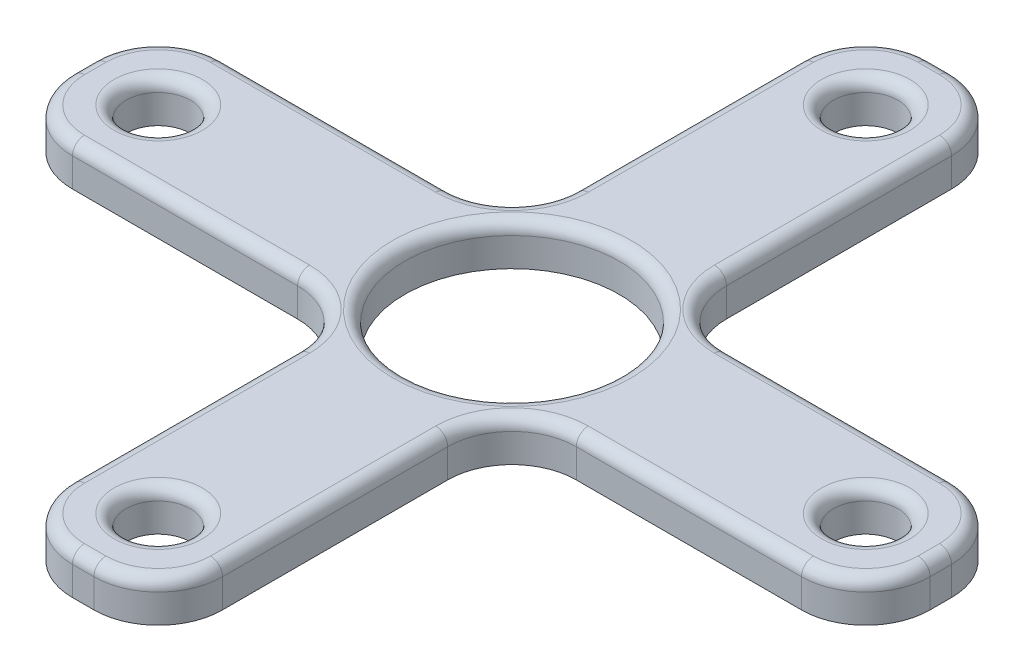
SolidWorks part; units mm, degrees
ref_plane "Front Plane" through (0, 0, 0) normal (0, 0, 1) x (1, 0, 0)
ref_plane "Top Plane" through (0, 0, 0) normal (0, 1, 0) x (1, 0, 0)
ref_plane "Right Plane" through (0, 0, 0) normal (1, 0, 0) x (0, 0, -1)
sketch "Sketch1" plane through (0, 0, 0) normal (0, 1, 0) x (1, 0, 0)
  line L0 (-7.1392, 20) -> (-7.1392, 18) construction
  line L1 (12.8608, 0) -> (10.8608, 0) construction
  line L2 (-27.1392, 0) -> (-25.1392, 0) construction
  line L3 (-7.1392, 20) -> (-3.6392, 20)
  line L4 (-7.1392, 20) -> (-10.6392, 20)
  line L5 (-27.1392, 0) -> (-27.1392, 3.5)
  line L6 (-10.6392, 20) -> (-10.6392, 3.5)
  line L7 (-10.6392, 3.5) -> (-27.1392, 3.5)
  line L8 (-3.6392, 20) -> (-3.6392, 3.5)
  line L9 (-3.6392, 3.5) -> (12.8608, 3.5)
  line L10 (12.8608, 3.5) -> (12.8608, 0)
  line L11 (12.8608, 0) -> (12.8608, -3.5)
  line L12 (12.8608, -3.5) -> (-3.6392, -3.5)
  line L13 (-3.6392, -3.5) -> (-3.6392, -20)
  line L14 (-3.6392, -20) -> (-7.1392, -20)
  line L15 (-7.1392, -20) -> (-10.6392, -20)
  line L16 (-10.6392, -20) -> (-10.6392, -3.5)
  line L17 (-10.6392, -3.5) -> (-27.1392, -3.5)
  line L18 (-27.1392, -3.5) -> (-27.1392, 0)
  line L19 (-7.1392, -20) -> (-7.1392, -18) construction
  line L20 (-7.1392, 0) -> (-4.0464, 0) construction
  line L21 (-7.1392, 0) -> (-7.1392, 3.0617) construction
  line L22 (-25.1392, 0) -> (-23.6392, 0) construction
  line L23 (-7.1392, 18) -> (-7.1392, 16.5) construction
  line L24 (10.8608, 0) -> (9.3608, 0) construction
  line L25 (-7.1392, -18) -> (-7.1392, -16.5) construction
  circle A0 centre (-23.6392, 0) radius 1.5
  circle A1 centre (-7.1392, 16.5) radius 1.5
  circle A2 centre (9.3608, 0) radius 1.5
  circle A3 centre (-7.1392, -16.5) radius 1.5
  dimension "D1" = 3.5
  dimension "D2" = 3.5
  dimension "D3" = 2
  dimension "D4" = 3.5
  dimension "D5" = 3.5
  dimension "D6" = 2
  dimension "D7" = 2
  dimension "D8" = 2
  dimension "D9" = 1.5
  dimension "D10" = 1.5
  dimension "D11" = 1.5
  dimension "D12" = 1.5
extrude "Boss-Extrude1" add sketch "Sketch1" along normal blind 1.9
fillet "Fillet1" radius 3 8 edges at (-27.1392, 0.95, 3.5) (-27.1392, 0.95, -3.5) (-10.6392, 0.95, -20) (-3.6392, 0.95, -20) (12.8608, 0.95, -3.5) (12.8608, 0.95, 3.5) (-10.6392, 0.95, 20) (-3.6392, 0.95, 20)
fillet "Fillet3" radius 3 4 edges at (-3.6392, 0.95, -3.5) (-10.6392, 0.95, -3.5) (-10.6392, 0.95, 3.5) (-3.6392, 0.95, 3.5)
sketch "Sketch2" plane through (0, 1.9, 0) normal (0, 1, 0) x (1, 0, 0)
  line L0 (-7.1392, 15) -> (-7.1392, -15) construction
  circle A0 centre (-7.1392, 16.5) radius 1.5 construction
  circle A1 centre (-7.1392, -16.5) radius 1.5 construction
  circle A2 centre (-7.1392, 0) radius 5
  dimension "D1" = 10
extrude "Cut-Extrude1" cut sketch "Sketch2" against normal blind 1.9
fillet "Fillet5" radius 0.56 29 edges at (-7.1392, 1.9, 18) (-7.1392, 1.9, -15) (-26.2605, 1.9, -2.6213) (-18.8892, 1.9, -3.5) (-11.5179, 1.9, -4.3787) (-10.6392, 1.9, -11.75) (-9.7605, 1.9, -19.1213) (-7.1392, 1.9, -20) (-4.5179, 1.9, -19.1213) (-3.6392, 1.9, -11.75) (-2.7605, 1.9, -4.3787) (4.6108, 1.9, -3.5) (11.9821, 1.9, -2.6213) (12.8608, 1.9, 0) (11.9821, 1.9, 2.6213) (4.6108, 1.9, 3.5) (-2.7605, 1.9, 4.3787) (-3.6392, 1.9, 11.75) (-4.5179, 1.9, 19.1213) (-7.1392, 1.9, 20) (-9.7605, 1.9, 19.1213) (-10.6392, 1.9, 11.75) (-11.5179, 1.9, 4.3787) (-18.8892, 1.9, 3.5) (-26.2605, 1.9, 2.6213) (-27.1392, 1.9, 0) (-23.6392, 1.9, 1.5) (9.3608, 1.9, 1.5) (-7.1392, 1.9, 5)
